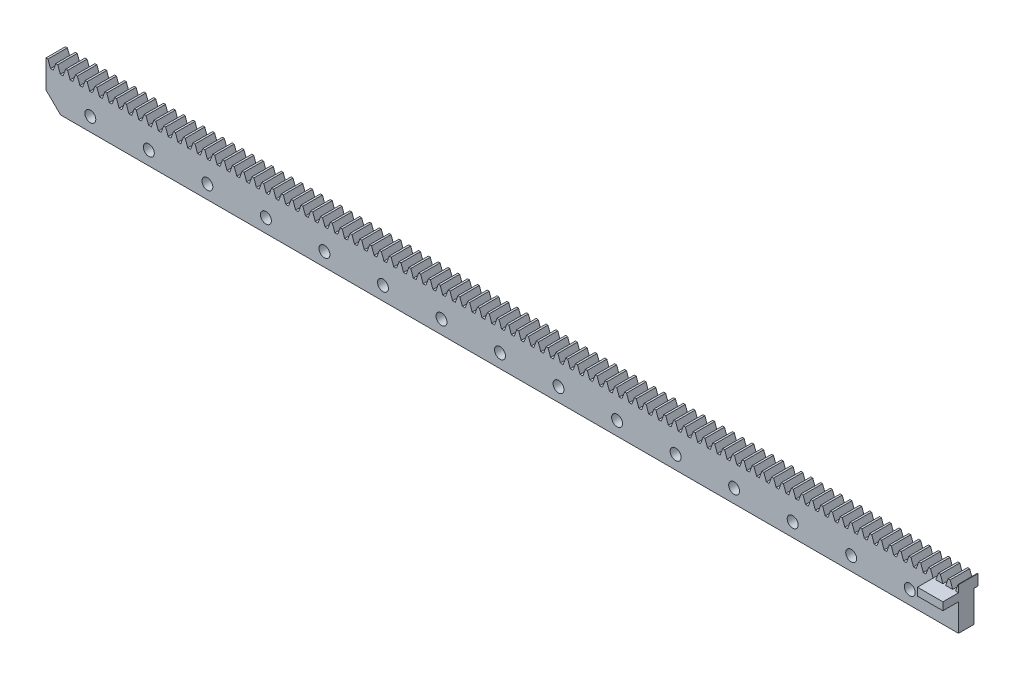
SolidWorks part; units mm, degrees
extrude "Blank" add sketch "BlankSke" against normal blind 5
sketch "BlankSke" plane through (0, 0, 0) normal (0, 0, 1) x (1, 0, 0)
  line L1 (0, 0) -> (260, 0)
  line L2 (0, 0) -> (0, 10.8)
  line L3 (0, 10.8) -> (260, 10.8)
  line L4 (260, 0) -> (260, 10.8)
  dimension "Length" = 260
  dimension "Blank_height" = 10.8
ref_plane "Plane1" through (0, 0, 0) normal (0, 0, 1) x (1, 0, 0)
ref_plane "Plane2" through (0, 0, 0) normal (0, 1, 0) x (1, 0, 0)
ref_plane "Plane3" through (0, 0, 0) normal (1, 0, 0) x (0, 0, -1)
other "Configuration Table"
sketch "HoldingSke" plane through (0, 0, 0) normal (0, 1, 0) x (1, 0, 0)
  line L0 (0, 0) -> (0.174, 1.2378)
  line L1 (-15, 0) -> (100, 0) construction
  line L2 (0, 0) -> (-2.1039, 2.3779)
  line L3 (0, 0) -> (-11.863, 4.5341)
  line L4 (0, 0) -> (-2.2351, 8.3417)
  line L5 (0, 0) -> (-23.7986, -8.8762)
  line L6 (0, 0) -> (-10.5278, -7.1032)
  line L9 (-71.009, 38.7566) -> (173.3111, 127.6818)
  line L10 (-76.2, 3.1779) -> (-66.2, 3.1779)
  line L11 (0, 0) -> (-5, 0)
  line L12 (-76.2, 101.6) -> (-76.17, 101.6)
  line L13 (24.9733, 27.94) -> (52.9518, 28.4284)
  line L14 (24.9733, 27.94) -> (24.9743, 27.94)
  line L15 (24.9733, 27.94) -> (100.4006, 29.5858)
  circle A0 centre (0, 0) radius 19.05
  circle A1 centre (0, 0) radius 5
  circle A2 centre (0, 0) radius 12.7
  dimension "MPH" = 10
  dimension "Diameter" = 38.1
  dimension "Num_teeth" = 105
  dimension "Pitch" = 1.25
  dimension "Show_teeth" = 998
  dimension "Thickness" = 12.7
  dimension "Ap" = 20
  dimension "Pitch_height" = 10
  dimension "Width" = 5
  dimension "Backlash" = 0.03
  dimension "Addendum_fac" = 1
  dimension "Dedendum_fac" = 1.25
  dimension "Clearance_fac" = 0.25
  dimension "Dedendum_add" = 0.001
  dimension "Length" = 260
  dimension "Module" = 0.8
sketch "TooCutSkeIll" plane through (0, 0, 0) normal (0, 0, 1) x (1, 0, 0)
  line L0 (-1.0018, 10.7789) -> (-0.4025, 9.1323)
  line L1 (-0.2136, 9) -> (0.2136, 9)
  line L2 (0.4025, 9.1323) -> (1.0018, 10.7789)
  line L3 (260, 10.8) -> (0, 10.8) construction
  line L4 (0, 0) -> (0, 64.897) construction
  line L5 (-13.208, 10) -> (12.954, 10) construction
  line L6 (0, 0) -> (260, 0) construction
  line L7 (0.7183, 10) -> (0.7183, 48.7463) construction
  line L8 (-0.7183, 10) -> (-0.7183, 48.7463) construction
  line L9 (1.0319, 10.8) -> (1.0319, 10.8254)
  line L10 (-1.0319, 10.8) -> (-1.0319, 10.8254)
  line L11 (-1.0319, 10.8254) -> (1.0319, 10.8254)
  arc A0 (0.2136, 9) -> (0.4025, 9.1323) centre (0.2136, 9.201) ccw
  arc A1 (-0.4025, 9.1323) -> (-0.2136, 9) centre (-0.2136, 9.201) ccw
  arc A2 (1.0319, 10.8) -> (1.0018, 10.7789) centre (1.0319, 10.768) ccw
  arc A3 (-1.0018, 10.7789) -> (-1.0319, 10.8) centre (-1.0319, 10.768) ccw
  dimension "Pitch_height" = 10
  dimension "Addendum_plus" = 0.8254
  dimension "Pressure_angle" = 20
  dimension "Gap_width" = 1.4366
  dimension "Dedendum" = 1
extrude "ToothCutIll" [suppressed] cut sketch "TooCutSkeIll" against normal through all
sketch "TooCutSkeSim" plane through (0, 0, 0) normal (0, 0, 1) x (1, 0, 0)
  line L0 (0.3543, 9) -> (-0.3543, 9)
  line L1 (1.0187, 10.8254) -> (0.3543, 9)
  line L2 (0, 17.4625) -> (0, 53.467) construction
  line L3 (1.0187, 10.8254) -> (-1.0187, 10.8254)
  line L6 (-1.0187, 10.8254) -> (-0.3543, 9)
  line L9 (-0.7183, 10) -> (0.7183, 10) construction
  line L10 (0, 0) -> (260, 0) construction
  line L11 (0.7183, 10) -> (0.7183, 53.467) construction
  line L12 (-0.7183, 10) -> (-0.7183, 53.467) construction
  dimension "Pitch_height" = 10
  dimension "Addendum_plus" = 0.8254
  dimension "Pressure_angle" = 20
  dimension "Gap_width" = 1.4366
  dimension "Dedendum" = 1
extrude "ToothCutSim" cut sketch "TooCutSkeSim" against normal through all
pattern_linear "TeethCuts" count 104 spacing 2.5133 along (1, 0, 0) of "ToothCutIll", "ToothCutSim"
sketch "草图4" plane through (0, 0, 0) normal (0, 0, 1) x (1, 0, 0)
  line L0 (29.867, 0) -> (26.1422, 3.6726)
  line L1 (0, 0) -> (260, 0) construction
  line L2 (26.1422, 3.6726) -> (26.1422, 10.8)
  line L3 (26.1422, 10.8) -> (0, 10.8)
  line L4 (0, 10.8) -> (0, 0)
  line L5 (0, 0) -> (29.867, 0)
extrude "切除-拉伸1" cut sketch "草图4" against normal blind 10
sketch "草图5" plane through (0, 0, 0) normal (0, 0, 1) x (1, 0, 0)
  circle A0 centre (247.5, 3.5) radius 1.4
  circle A1 centre (232.5, 3.5) radius 1.4
  circle A2 centre (217.5, 3.5) radius 1.4
  circle A3 centre (202.5, 3.5) radius 1.4
  circle A4 centre (187.5, 3.5) radius 1.4
  circle A5 centre (172.5, 3.5) radius 1.4
  circle A6 centre (157.5, 3.5) radius 1.4
  circle A7 centre (142.5, 3.5) radius 1.4
  circle A8 centre (127.5, 3.5) radius 1.4
  circle A9 centre (112.5, 3.5) radius 1.4
  circle A10 centre (97.5, 3.5) radius 1.4
  circle A11 centre (82.5, 3.5) radius 1.4
  circle A12 centre (67.5, 3.5) radius 1.4
  circle A13 centre (52.5, 3.5) radius 1.4
  circle A14 centre (37.5, 3.5) radius 1.4
  dimension "D1" = 2.8
  dimension "D2" = 15
extrude "切除-拉伸2" cut sketch "草图5" against normal through all
sketch "草图6" plane through (260, 0, 0) normal (1, 0, 0) x (0, 0, -1)
  line L1 (5, 0) -> (4, 0)
  line L2 (5, 0) -> (5, 8)
  line L3 (5, 8) -> (4, 8)
  line L4 (4, 0) -> (4, 8)
  dimension "D1" = 1
  dimension "D2" = 8
extrude "切除-拉伸3" cut sketch "草图6" against normal blind 200
sketch "草图7" plane through (0, 0, 0) normal (0, 0, 1) x (1, 0, 0)
  line L0 (260, 0) -> (260, 10.8) construction
  line L1 (260, 7.0175) -> (253.4863, 7.0175)
  line L2 (260, 7.0175) -> (260, 9)
  line L3 (260, 9) -> (253.4863, 9)
  line L4 (253.4863, 7.0175) -> (253.4863, 9)
extrude "凸台-拉伸1" add sketch "草图7" along normal blind 4
equation "' \"Module@HoldingSke\" = 6.35"
equation "' \"Num_teeth@HoldingSke\" = 12"
equation "' \"Ap@HoldingSke\" =  20"
equation "' \"Ap@HoldingSke\" = 20"
equation "' \"Width@HoldingSke\" = 0.25 * 25.4"
equation "' \"Show_teeth@HoldingSke\" = 500"
equation "' \"Backlash@HoldingSke\" = 0.009 * 25.4"
equation "' \"Addendum_fac@HoldingSke\" = 1.0"
equation "' \"Dedendum_fac@HoldingSke\" = 1.25"
equation "' \"Dedendum_add@HoldingSke\" = 0.00005 * 25.4"
equation "' \"Clearance_fac@HoldingSke\" = 0.25"
equation "' \"Pitch_height@HoldingSke\" = 1 * 25.4"
equation "' \"Length@HoldingSke\" = 4.71 * 25.4"
equation "\"Pitch@HoldingSke\" = 1 / \"Module@HoldingSke\""
equation "\"MPH@HoldingSke\" = \"Dedendum_fac@HoldingSke\" / \"Pitch@HoldingSke\" + 2 * \"Dedendum_add@HoldingSke\" + 0.002 * 25.4"
equation "\"MPH@HoldingSke\" = ((sgn( \"MPH@HoldingSke\" - \"Pitch_height@HoldingSke\")+1)*( \"MPH@HoldingSke\" - \"Pitch_height@HoldingSke\"))/2 + \"Pitch_height@HoldingSke\""
equation "\"Blank_height@BlankSke\" = \"Pitch_height@HoldingSke\" + \"Addendum_fac@HoldingSke\"  / \"Pitch@HoldingSke\" "
equation "\"Length@BlankSke\" =  \"Length@HoldingSke\""
equation "\"Face_width@Blank\" = \"Width@HoldingSke\""
equation "\"Pressure_angle@TooCutSkeIll\" = \"Ap@HoldingSke\""
equation "\"Addendum_plus@TooCutSkeIll\" =  \"Addendum_fac@HoldingSke\"  / \"Pitch@HoldingSke\" + 0.001 *25.4"
equation "\"Dedendum@TooCutSkeIll\" = \"Dedendum_fac@HoldingSke\"  / \"Pitch@HoldingSke\""
equation "\"Pitch_height@TooCutSkeIll\" =  \"MPH@HoldingSke\""
equation "\"Gap_width@TooCutSkeIll\" = 3.14159265 / 2 / \"Pitch@HoldingSke\" + 6 * \"Backlash@HoldingSke\""
equation "\"Pressure_angle@TooCutSkeSim\" = \"Ap@HoldingSke\""
equation "\"Addendum_plus@TooCutSkeSim\" =  \"Addendum_fac@HoldingSke\"  / \"Pitch@HoldingSke\" + 0.001 * 25.4"
equation "\"Dedendum@TooCutSkeSim\" = \"Dedendum_fac@HoldingSke\"  / \"Pitch@HoldingSke\""
equation "\"Pitch_height@TooCutSkeSim\" =  \"MPH@HoldingSke\""
equation "\"Gap_width@TooCutSkeSim\" = 3.14159265 / 2 / \"Pitch@HoldingSke\" + 6 * \"Backlash@HoldingSke\""
equation "\"Root_fillet@TooCutSkeIll\" = \"Clearance_fac@HoldingSke\" / \"Pitch@HoldingSke\" + \"Dedendum_add@HoldingSke\""
equation "\"Break_rad@TooCutSkeIll\" = 0.02 / \"Pitch@HoldingSke\" * 2"
equation "\"Linear_pitch@TeethCuts\" = 3.14159265 / \"Pitch@HoldingSke\""
equation "\"Num_teeth@HoldingSke\" = int( ( \"Length@HoldingSke\" + 0 ) / (3.14159265 / \"Pitch@HoldingSke\")) + 0.9999  + 1"
equation " \"Num_teeth@TeethCuts\" = int( \"Show_teeth@HoldingSke\" ) + 1"
equation " \"Num_teeth@TeethCuts\" = ((sgn( \"Num_teeth@TeethCuts\" - \"Num_teeth@HoldingSke\" )-1)*( \"Num_teeth@TeethCuts\" - \"Num_teeth@HoldingSke\" ))/-2+ \"Num_teeth@HoldingSke\""
equation " \"Num_teeth@TeethCuts\" = ((sgn( \"Num_teeth@TeethCuts\" - 2.0)+1)*( \"Num_teeth@TeethCuts\" - 2.0))/2 +2.0"
